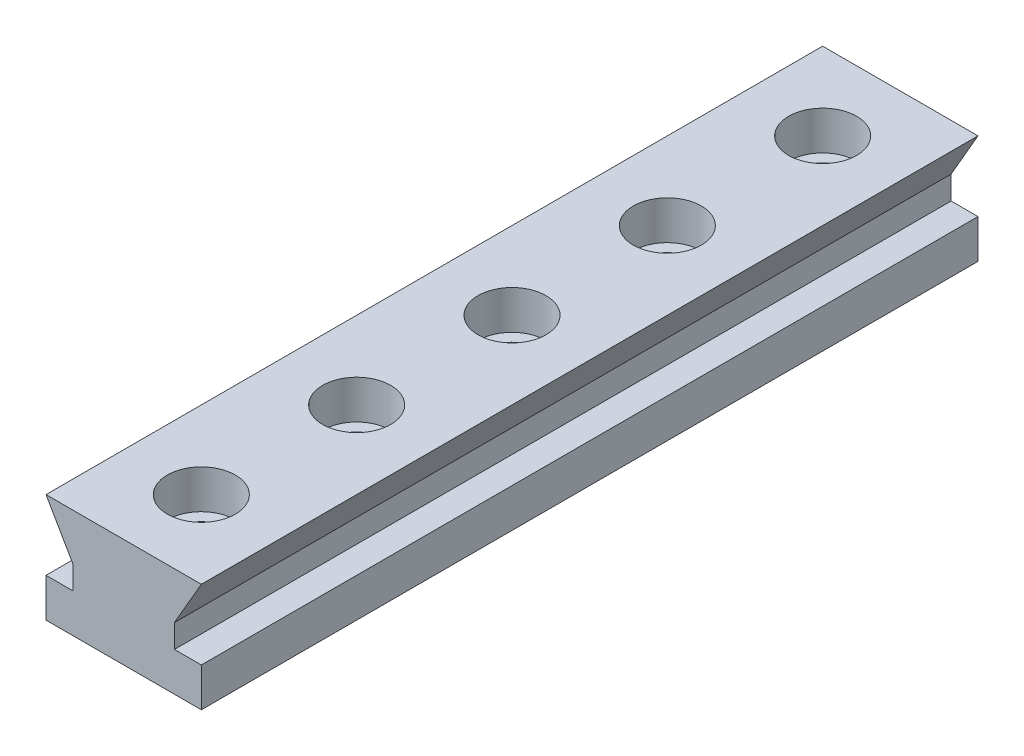
SolidWorks part; units mm, degrees
ref_plane "Front Plane" through (0, 0, 0) normal (0, 0, 1) x (1, 0, 0)
ref_plane "Top Plane" through (0, 0, 0) normal (0, 1, 0) x (1, 0, 0)
ref_plane "Right Plane" through (0, 0, 0) normal (1, 0, 0) x (0, 0, -1)
sketch "Sketch1" plane through (0, 0, 0) normal (0, 0, 1) x (1, 0, 0)
  line L0 (0, 0) -> (25.4, 0)
  line L1 (25.4, 0) -> (21.0006, -7.62)
  line L2 (21.0006, -7.62) -> (21.0006, -11.43)
  line L3 (21.0006, -11.43) -> (25.4, -11.43)
  line L4 (25.4, -11.43) -> (25.4, -17.78)
  line L5 (25.4, -17.78) -> (0, -17.78)
  line L6 (0, -17.78) -> (0, -11.43)
  line L7 (0, -11.43) -> (4.3994, -11.43)
  line L8 (4.3994, -11.43) -> (4.3994, -7.62)
  line L9 (4.3994, -7.62) -> (0, 0)
  dimension "D1" = 60
  dimension "D2" = 60
  dimension "D3" = 25.4
  dimension "D4" = 7.62
  dimension "D5" = 7.62
  dimension "D6" = 3.81
  dimension "D7" = 3.81
  dimension "D8" = 6.35
extrude "Boss-Extrude1" add sketch "Sketch1" along normal blind 127
hole_wizard "CBORE for 1/4 Socket Head Cap Screw1" positions "Sketch3" profile "Sketch4" counterbore size "1/4" standard "ANSI Inch" end condition up to next
sketch "Sketch3" plane through (0, 0, 0) normal (0, 1, 0) x (1, 0, 0)
  line L0 (25.4, 0) -> (0, 0) construction
  line L1 (0, -127) -> (0, 0) construction
  point P0 (12.7, -12.7)
  point P2 (12.7, -38.1)
  point P4 (12.7, -63.5)
  point P6 (12.7, -88.9)
  point P12 (12.7, -114.3)
  dimension "D1" = 25.4
  dimension "D2" = 25.4
  dimension "D3" = 25.4
  dimension "D4" = 12.7
  dimension "D5" = 25.4
  dimension "D6" = 12.7
sketch "Sketch4" plane through (12.7, 0, 12.7) normal (1, 0, 0) x (0, 0, 1)
  line L0 (0, 0) -> (0, 17.78)
  line L1 (0, 17.78) -> (3.5712, 17.78)
  line L3 (3.5712, 17.78) -> (3.5712, 6.35)
  line L4 (3.5712, 6.35) -> (5.5562, 6.35)
  line L5 (5.5562, 6.35) -> (5.5563, 0)
  line L7 (5.5563, 0) -> (0, 0)
  line L11 (0, -6.35) -> (0, 107.95) construction
  dimension "Thru Hole Dia." = 7.1425
  dimension "Thru Hole Depth" = 17.78
  dimension "C'Bore Dia." = 11.1125
  dimension "C'Bore Depth" = 6.35
